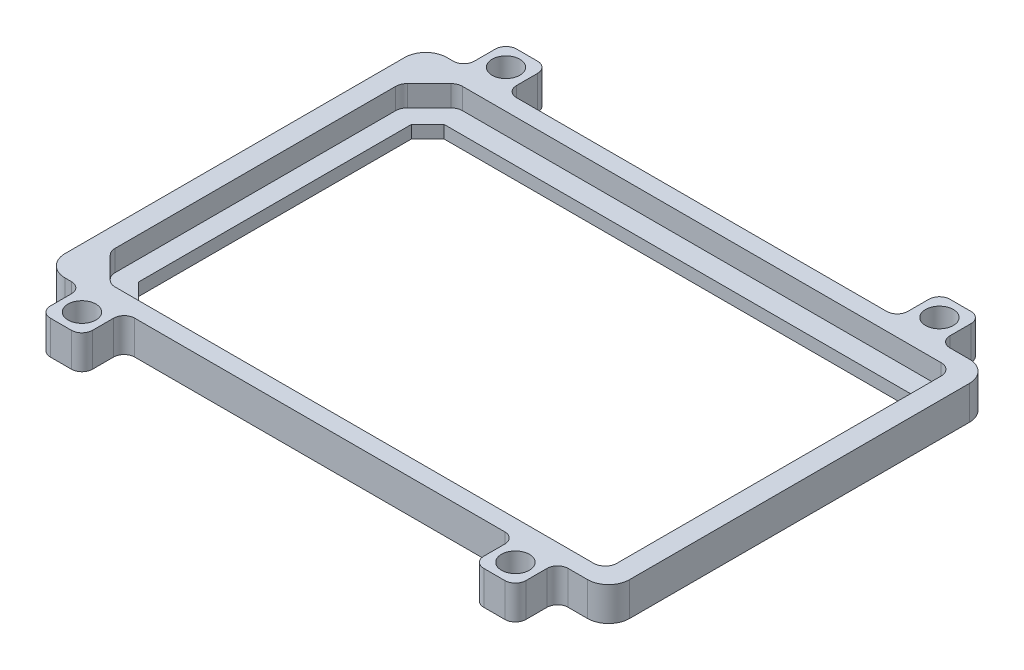
SolidWorks part; units mm, degrees
ref_plane "Front Plane" through (0, 0, 0) normal (0, 0, 1) x (1, 0, 0)
ref_plane "Top Plane" through (0, 0, 0) normal (0, 1, 0) x (1, 0, 0)
ref_plane "Right Plane" through (0, 0, 0) normal (1, 0, 0) x (0, 0, -1)
sketch "Sketch1" plane through (0, 0, 0) normal (0, 1, 0) x (1, 0, 0)
  line L1 (0, 0) -> (157.0786, 0)
  line L2 (0, 0) -> (0, -90.551)
  line L3 (0, -90.551) -> (157.0786, -90.551)
  line L4 (157.0786, 0) -> (157.0786, -90.551)
  dimension "D1" = 157.0786
  dimension "D2" = 90.551
extrude "Boss-Extrude1" add sketch "Sketch1" along normal blind 8
sketch "Sketch7" plane through (0, 0, 0) normal (0, -1, 0) x (1, 0, 0)
  circle A0 centre (33.602, 72.2755) radius 8.95
  circle A1 centre (33.602, 18.2755) radius 8.5
  circle A2 centre (51.692, 72.2755) radius 8.95
  circle A3 centre (69.782, 72.2755) radius 8.95
  circle A4 centre (87.872, 72.2755) radius 8.95
  circle A5 centre (105.962, 72.2755) radius 8.95
  circle A6 centre (124.052, 72.2755) radius 8.95
  circle A7 centre (51.692, 54.2755) radius 8.95
  circle A8 centre (69.782, 54.2755) radius 8.95
  circle A9 centre (87.872, 54.2755) radius 8.95
  circle A10 centre (105.962, 54.2755) radius 8.95
  circle A11 centre (124.052, 54.2755) radius 8.95
  circle A12 centre (51.692, 36.2755) radius 8.95
  circle A13 centre (69.782, 36.2755) radius 8.95
  circle A14 centre (87.872, 36.2755) radius 8.95
  circle A15 centre (105.962, 36.2755) radius 8.95
  circle A16 centre (124.052, 36.2755) radius 8.95
  circle A17 centre (51.692, 18.2755) radius 8.95
  circle A18 centre (69.782, 18.2755) radius 8.95
  circle A19 centre (87.872, 18.2755) radius 8.95
  circle A20 centre (105.962, 18.2755) radius 8.95
  circle A21 centre (124.052, 18.2755) radius 8.95
  circle A22 centre (33.602, 54.2755) radius 8.95
  circle A23 centre (33.602, 36.2755) radius 8.95
  circle A24 centre (33.602, 18.2755) radius 8.95
  circle A25 centre (51.692, 18.2755) radius 8.5
  circle A26 centre (69.782, 18.2755) radius 8.5
  circle A27 centre (87.872, 18.2755) radius 8.5
  circle A28 centre (105.962, 18.2755) radius 8.5
  circle A29 centre (124.052, 18.2755) radius 8.5
  circle A30 centre (33.602, 36.2755) radius 8.5
  circle A31 centre (51.692, 36.2755) radius 8.5
  circle A32 centre (69.782, 36.2755) radius 8.5
  circle A33 centre (87.872, 36.2755) radius 8.5
  circle A34 centre (105.962, 36.2755) radius 8.5
  circle A35 centre (124.052, 36.2755) radius 8.5
  circle A36 centre (33.602, 54.2755) radius 8.5
  circle A37 centre (51.692, 54.2755) radius 8.5
  circle A38 centre (69.782, 54.2755) radius 8.5
  circle A39 centre (87.872, 54.2755) radius 8.5
  circle A40 centre (105.962, 54.2755) radius 8.5
  circle A41 centre (124.052, 54.2755) radius 8.5
  circle A42 centre (124.052, 72.2755) radius 8.5
  circle A43 centre (105.962, 72.2755) radius 8.5
  circle A44 centre (87.872, 72.2755) radius 8.5
  circle A45 centre (69.782, 72.2755) radius 8.5
  circle A46 centre (51.692, 72.2755) radius 8.5
  circle A47 centre (33.602, 72.2755) radius 8.5
  dimension "D1" = 17.9
  dimension "D2" = 17
  dimension "D6" = 18
  dimension "D3" = 18.09
  dimension "D4" = 18
  dimension "D5" = 18.09
  dimension "D7" = 6
  dimension "D8" = 4
sketch "Sketch23" plane through (0, 8, 0) normal (0, 1, 0) x (1, 0, 0)
  line L1 (140.6288, -86.4755) -> (23.2359, -86.4755)
  line L2 (140.6288, -86.4755) -> (140.6288, -4.0755)
  line L3 (140.6288, -4.0755) -> (23.2359, -4.0755)
  line L4 (16.4498, -79.6894) -> (16.4498, -10.8616)
  line L5 (16.4498, -10.8616) -> (23.2359, -4.0755)
  line L6 (23.2359, -4.0755) -> (16.4498, -4.0755) construction
  line L7 (16.4498, -4.0755) -> (16.4498, -10.8616) construction
  line L8 (23.2359, -86.4755) -> (16.4498, -79.6894)
  line L10 (157.0786, 0) -> (0, 0) construction
  line L11 (140.6288, -4.0755) -> (140.6288, 0) construction
  line L12 (23.2359, -86.4755) -> (16.4498, -86.4755) construction
  line L13 (16.4498, -86.4755) -> (16.4498, -79.6894) construction
  line L14 (157.0786, -90.551) -> (157.0786, 0) construction
  line L15 (140.6288, -86.4755) -> (157.0786, -86.4755) construction
  line L16 (16.4498, -86.4755) -> (0, -86.4755) construction
  line L17 (0, 0) -> (0, -90.551) construction
  line L18 (157.0786, 0) -> (0, 0) construction
  line L19 (140.6288, -86.4755) -> (140.6288, -90.551) construction
  line L20 (0, -90.551) -> (157.0786, -90.551) construction
  dimension "D2" = 124.179
  dimension "D3" = 9.597
  dimension "D5" = 9.597
  dimension "D9" = 82.4
  dimension "D10" = 4.0755
extrude "Cut-Extrude21" cut sketch "Sketch23" against normal blind 5
fillet "Fillet8" radius 2.75 6 edges at (140.6288, 5.5, 4.0755) (16.4498, 5.5, 10.8616) (23.2359, 5.5, 4.0755) (140.6288, 5.5, 86.4755) (23.2359, 5.5, 86.4755) (16.4498, 5.5, 79.6894)
sketch "Sketch29" plane through (0, 8, 0) normal (0, 1, 0) x (1, 0, 0)
  line L0 (157.0786, 0) -> (0, 0) construction
  line L1 (157.0786, -90.551) -> (145.4887, -90.551)
  line L2 (157.0786, -90.551) -> (157.0786, 0)
  line L3 (157.0786, 0) -> (145.4887, 0)
  line L4 (145.4887, -90.551) -> (145.4887, 0)
  line L6 (0, -90.551) -> (11.5899, -90.551)
  line L7 (0, -90.551) -> (0, 0)
  line L8 (0, 0) -> (11.5899, 0)
  line L9 (11.5899, -90.551) -> (11.5899, 0)
  dimension "D2" = 4.0755
extrude "Cut-Extrude25" cut sketch "Sketch29" against normal through all
fillet "Fillet9" radius 5 4 edges at (145.4887, 4, 90.551) (145.4887, 4, 0) (11.5899, 4, 90.551) (11.5899, 4, 0)
sketch "Sketch36" plane through (0, 0, 0) normal (0, -1, 0) x (1, 0, 0)
  line L0 (16.5899, 90.551) -> (140.4887, 90.551) construction
  line L1 (20.6082, 90.551) -> (30.6082, 90.551)
  line L2 (20.6082, 90.551) -> (20.6082, 100.551)
  line L3 (20.6082, 100.551) -> (30.6082, 100.551)
  line L4 (30.6082, 90.551) -> (30.6082, 100.551)
  line L5 (140.4887, 0) -> (16.5899, 0) construction
  line L6 (123.3943, 90.551) -> (133.3943, 90.551)
  line L7 (123.3943, 90.551) -> (123.3943, 100.551)
  line L8 (123.3943, 100.551) -> (133.3943, 100.551)
  line L9 (133.3943, 90.551) -> (133.3943, 100.551)
  line L10 (30.6082, 0) -> (20.6082, 0)
  line L11 (30.6082, 0) -> (30.6082, -10)
  line L12 (30.6082, -10) -> (20.6082, -10)
  line L13 (20.6082, 0) -> (20.6082, -10)
  line L14 (11.5899, 85.551) -> (11.5899, 5) construction
  line L15 (123.3943, 0) -> (133.3943, 0)
  line L16 (123.3943, 0) -> (123.3943, -10)
  line L17 (123.3943, -10) -> (133.3943, -10)
  line L18 (133.3943, 0) -> (133.3943, -10)
  line L19 (145.4887, 5) -> (145.4887, 85.551) construction
  line L22 (133.3943, 90.551) -> (123.3943, 100.551) construction
  line L23 (123.3943, 90.551) -> (133.3943, 100.551) construction
  line L24 (30.6082, 100.551) -> (20.6082, 90.551) construction
  line L25 (30.6082, 90.551) -> (20.6082, 100.551) construction
  line L26 (20.6082, 0) -> (30.6082, -10) construction
  line L27 (30.6082, 0) -> (20.6082, -10) construction
  line L28 (20.6082, -10) -> (21.4692, -10.0262) construction
  line L29 (133.3943, 0) -> (123.3943, -10) construction
  line L30 (133.3943, -10) -> (123.3943, 0) construction
  circle A0 centre (128.3943, -5) radius 3.3
  circle A1 centre (25.6082, -5) radius 3.3
  circle A2 centre (25.6082, 95.551) radius 3.3
  circle A3 centre (128.3943, 95.551) radius 3.3
  point P24 (11.5899, 45.2755)
  point P25 (145.4887, 45.2755)
  dimension "D5" = 6.6
  dimension "D9" = 6.6
  dimension "D10" = 7.0944
  dimension "D2" = 102.7861
  dimension "D3" = 10
  dimension "D4" = 10
  dimension "D6" = 4.0183
  dimension "D7" = 4.0183
  dimension "D8" = 7.0944
  dimension "D11" = 102.7861
  dimension "D12" = 14.0183
  dimension "D13" = 17.0944
  dimension "D14" = 133.8987
extrude "Boss-Extrude10" add sketch "Sketch36" against normal up to surface (8 mm away) up to face at (78.5393, 8, 45.2755)
fillet "Fillet10" radius 2.5 16 edges at (20.6082, 4, 100.551) (30.6082, 4, 100.551) (123.3943, 4, 100.551) (133.3943, 4, 100.551) (133.3943, 4, -10) (123.3943, 4, -10) (30.6082, 4, -10) (20.6082, 4, -10) (123.3943, 4, 90.551) (20.6082, 4, 90.551) (133.3943, 4, 90.551) (30.6082, 4, 90.551) (133.3943, 4, 0) (123.3943, 4, 0) (30.6082, 4, 0) (20.6082, 4, 0)
sketch "Sketch37" plane through (0, 3, 0) normal (0, 1, 0) x (1, 0, 0)
  line L30 (21.1393, -77.6183) -> (24.9965, -81.4755)
  line L31 (24.9965, -81.4755) -> (135.9393, -81.4755)
  line L32 (135.9393, -81.4755) -> (135.9393, -9.0755)
  line L33 (135.9393, -9.0755) -> (24.9965, -9.0755)
  line L34 (21.1393, -12.9327) -> (21.1393, -77.6183)
  line L35 (24.9965, -9.0755) -> (21.1393, -12.9327)
  line L36 (71.1735, -4.0755) -> (71.1735, -9.0755) construction
  line L37 (137.8788, -4.0755) -> (24.375, -4.0755) construction
  line L38 (73.2334, -81.4755) -> (73.2334, -86.4755) construction
  line L39 (24.375, -86.4755) -> (137.8788, -86.4755) construction
  line L40 (16.4498, -38.7906) -> (21.1393, -38.7906) construction
  line L41 (16.4498, -12.0007) -> (16.4498, -78.5503) construction
  line L42 (135.9393, -38.7906) -> (140.6288, -38.7906) construction
  line L43 (140.6288, -83.7255) -> (140.6288, -6.8255) construction
  dimension "D1" = 110.9428
  dimension "D2" = 110.9428
  dimension "D3" = 72.4
  dimension "D4" = 64.6856
  dimension "D5" = 5.4549
extrude "Cut-Extrude26" cut sketch "Sketch37" against normal up to next (3 mm away) from surface at 0 starting at face at (59.8857, 3, 45.2755)
